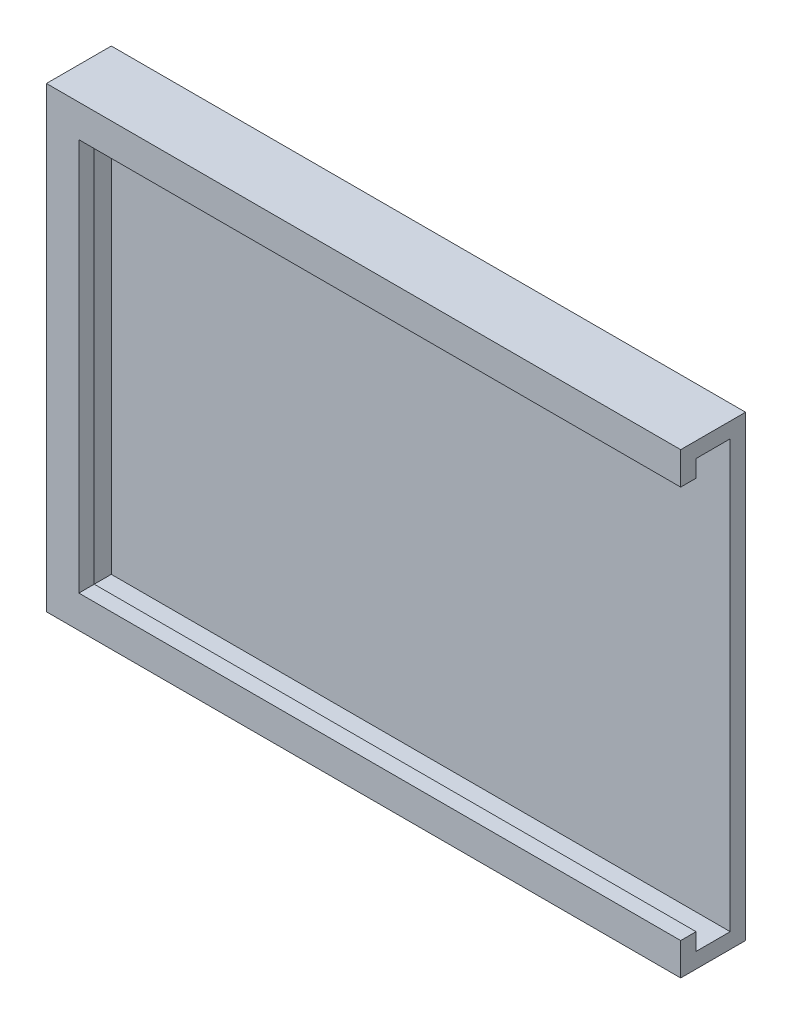
SolidWorks part; units mm, degrees
ref_plane "前视基准面" through (0, 0, 0) normal (0, 0, 1) x (1, 0, 0)
ref_plane "上视基准面" through (0, 0, 0) normal (0, 1, 0) x (1, 0, 0)
ref_plane "右视基准面" through (0, 0, 0) normal (1, 0, 0) x (0, 0, -1)
sketch "草图1" plane through (0, 0, 0) normal (0, 0, 1) x (1, 0, 0)
  line L1 (-36.25, 25) -> (36.25, 25)
  line L2 (-36.25, 25) -> (-36.25, -25)
  line L3 (-36.25, -25) -> (36.25, -25)
  line L4 (36.25, 25) -> (36.25, -25)
  line L5 (-36.25, 25) -> (36.25, -25) construction
  line L6 (-36.25, -25) -> (36.25, 25) construction
  point P0 (0, 0)
  dimension "D1" = 72.5
  dimension "D2" = 50
extrude "凸台-拉伸1" add sketch "草图1" along normal blind 4
shell "抽壳1" thickness 1.8
sketch "草图2" plane through (0, 0, 5.8) normal (0, 0, 1) x (1, 0, 0)
  line L4 (34.25, 23) -> (36.25, 23)
  line L5 (36.25, -26.8) -> (36.25, 26.8) construction
  line L6 (36.25, 23) -> (36.25, -23)
  line L7 (36.25, -23) -> (34.25, -23)
  line L8 (34.25, -23) -> (34.25, 23)
  line L9 (34.25, 23) -> (-34.25, 23)
  line L10 (-34.25, 23) -> (-34.25, -23)
  line L11 (-34.25, -23) -> (34.25, -23)
  line L13 (34.25, 23) -> (-34.25, 23)
  line L14 (-34.25, 23) -> (-34.25, -23)
  line L15 (-34.25, -23) -> (34.25, -23)
  dimension "D1" = 2
extrude "切除-拉伸1" cut sketch "草图2" against normal blind 4 and the other way through all
